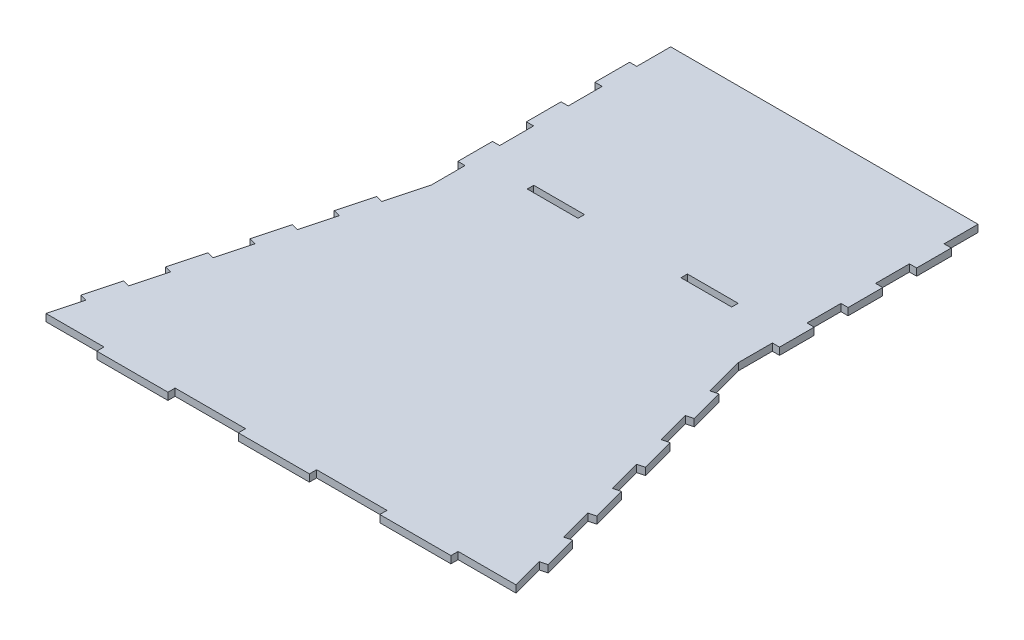
SolidWorks part; units mm, degrees
ref_plane "Front Plane" through (0, 0, 0) normal (0, 0, 1) x (1, 0, 0)
ref_plane "Top Plane" through (0, 0, 0) normal (0, 1, 0) x (1, 0, 0)
ref_plane "Right Plane" through (0, 0, 0) normal (1, 0, 0) x (0, 0, -1)
sketch "Sketch1" plane through (0, 0, 0) normal (0, 1, 0) x (1, 0, 0)
  line L0 (44.226, 0) -> (73.91, 0)
  line L1 (73.91, 0) -> (73.91, 3)
  line L3 (44.226, 3) -> (44.226, 0)
  line L4 (-14.842, 0) -> (14.842, 0)
  line L5 (14.842, 0) -> (14.842, 3)
  line L7 (-14.842, 3) -> (-14.842, 0)
  line L8 (-73.91, 0) -> (-44.226, 0)
  line L9 (-44.226, 0) -> (-44.226, 3)
  line L11 (-73.91, 3) -> (-73.91, 0)
  line L12 (-98.1297, 3) -> (-94.5922, 16.2024)
  line L13 (-94.5922, 16.2024) -> (-97.4899, 16.9788)
  line L14 (-97.4899, 16.9788) -> (-93.728, 31.0185)
  line L15 (-93.728, 31.0185) -> (-90.8303, 30.242)
  line L16 (-90.8303, 30.242) -> (-87.146, 43.9919)
  line L17 (-87.146, 43.9919) -> (-90.0438, 44.7684)
  line L18 (-90.0438, 44.7684) -> (-86.2819, 58.808)
  line L19 (-86.2819, 58.808) -> (-83.3841, 58.0316)
  line L20 (-83.3841, 58.0316) -> (-79.6998, 71.7814)
  line L21 (-79.6998, 71.7814) -> (-82.5976, 72.5579)
  line L22 (-82.5976, 72.5579) -> (-78.8357, 86.5976)
  line L23 (-78.8357, 86.5976) -> (-75.9379, 85.8211)
  line L24 (-75.9379, 85.8211) -> (-72.2536, 99.571)
  line L25 (-72.2536, 99.571) -> (-75.1514, 100.3474)
  line L26 (-75.1514, 100.3474) -> (-71.3895, 114.3871)
  line L27 (-71.3895, 114.3871) -> (-68.4917, 113.6106)
  line L28 (-68.4917, 113.6106) -> (-64.1503, 129.813)
  line L29 (-73.91, 3) -> (-98.1297, 3)
  line L30 (-44.226, 3) -> (-14.842, 3)
  line L31 (14.842, 3) -> (44.226, 3)
  line L32 (0, -16.1228) -> (0, 54.6201) construction
  line L33 (73.91, 3) -> (98.1297, 3)
  line L34 (-73.91, 3) -> (-44.526, 3) construction
  line L35 (-44.526, 3) -> (-44.226, 3) construction
  line L36 (-94.5922, 16.2024) -> (-90.9079, 29.9522) construction
  line L37 (-90.9079, 29.9522) -> (-90.8303, 30.242) construction
  line L38 (98.1297, 3) -> (94.5922, 16.2024)
  line L39 (90.9079, 29.9522) -> (90.8303, 30.242) construction
  line L40 (94.5922, 16.2024) -> (90.9079, 29.9522) construction
  line L41 (68.4917, 113.6106) -> (64.1503, 129.813)
  line L42 (71.3895, 114.3871) -> (68.4917, 113.6106)
  line L43 (75.1514, 100.3474) -> (71.3895, 114.3871)
  line L44 (72.2536, 99.571) -> (75.1514, 100.3474)
  line L45 (75.9379, 85.8211) -> (72.2536, 99.571)
  line L46 (78.8357, 86.5976) -> (75.9379, 85.8211)
  line L47 (82.5976, 72.5579) -> (78.8357, 86.5976)
  line L48 (79.6998, 71.7814) -> (82.5976, 72.5579)
  line L49 (83.3841, 58.0316) -> (79.6998, 71.7814)
  line L50 (86.2819, 58.808) -> (83.3841, 58.0316)
  line L51 (90.0438, 44.7684) -> (86.2819, 58.808)
  line L52 (87.146, 43.9919) -> (90.0438, 44.7684)
  line L53 (90.8303, 30.242) -> (87.146, 43.9919)
  line L54 (93.728, 31.0185) -> (90.8303, 30.242)
  line L55 (97.4899, 16.9788) -> (93.728, 31.0185)
  line L56 (94.5922, 16.2024) -> (97.4899, 16.9788)
  line L57 (-64.1503, 129.813) -> (-64.1503, 143.9701)
  line L58 (-64.1503, 143.9701) -> (-67.1503, 143.9701)
  line L59 (-67.1503, 143.9701) -> (-67.1503, 158.4273)
  line L60 (-67.1503, 158.4273) -> (-64.1503, 158.4273)
  line L61 (-64.1503, 158.4273) -> (-64.1503, 172.5844)
  line L62 (-64.1503, 172.5844) -> (-67.1503, 172.5844)
  line L63 (-67.1503, 172.5844) -> (-67.1503, 187.0416)
  line L64 (-67.1503, 187.0416) -> (-64.1503, 187.0416)
  line L65 (-64.1503, 187.0416) -> (-64.1503, 201.1987)
  line L66 (-64.1503, 201.1987) -> (-67.1503, 201.1987)
  line L67 (-67.1503, 201.1987) -> (-67.1503, 215.6559)
  line L68 (-67.1503, 215.6559) -> (-64.1503, 215.6559)
  line L69 (-64.1503, 215.6559) -> (-64.1503, 229.813)
  line L70 (-64.1503, 229.813) -> (64.1503, 229.813)
  line L71 (-64.1503, 143.9701) -> (-64.1503, 158.1273) construction
  line L72 (-64.1503, 158.1273) -> (-64.1503, 158.4273) construction
  line L73 (64.1503, 158.1273) -> (64.1503, 158.4273) construction
  line L74 (64.1503, 143.9701) -> (64.1503, 158.1273) construction
  line L75 (64.1503, 215.6559) -> (64.1503, 229.813)
  line L76 (67.1503, 215.6559) -> (64.1503, 215.6559)
  line L77 (67.1503, 201.1987) -> (67.1503, 215.6559)
  line L78 (64.1503, 201.1987) -> (67.1503, 201.1987)
  line L79 (64.1503, 187.0416) -> (64.1503, 201.1987)
  line L80 (67.1503, 187.0416) -> (64.1503, 187.0416)
  line L81 (67.1503, 172.5844) -> (67.1503, 187.0416)
  line L82 (64.1503, 172.5844) -> (67.1503, 172.5844)
  line L83 (64.1503, 158.4273) -> (64.1503, 172.5844)
  line L84 (67.1503, 158.4273) -> (64.1503, 158.4273)
  line L85 (67.1503, 143.9701) -> (67.1503, 158.4273)
  line L86 (64.1503, 143.9701) -> (67.1503, 143.9701)
  line L87 (64.1503, 129.813) -> (64.1503, 143.9701)
  line L88 (-42.6669, 148.463) -> (-21.4834, 148.463)
  line L89 (-42.6669, 148.463) -> (-42.6669, 151.163)
  line L90 (-21.4834, 148.463) -> (-21.4834, 151.163)
  line L91 (-42.6669, 151.163) -> (-21.4834, 151.163)
  line L92 (-42.6669, 149.813) -> (-64.1503, 149.813) construction
  line L93 (-21.4834, 149.813) -> (0, 149.813) construction
  line L94 (-21.4834, 150.488) -> (-42.9669, 150.488) construction
  line L95 (-42.9669, 150.488) -> (-42.6669, 150.488) construction
  line L96 (-21.4834, 149.813) -> (-42.6669, 151.163) construction
  line L97 (21.4834, 148.463) -> (21.4834, 151.163)
  line L98 (42.6669, 151.163) -> (21.4834, 151.163)
  line L99 (42.6669, 148.463) -> (42.6669, 151.163)
  line L100 (42.6669, 148.463) -> (21.4834, 148.463)
  point P32 (0, 0)
  point P85 (0, 229.813)
  point P95 (-32.0751, 150.488)
  dimension "D1" = 75
  dimension "D2" = 196.2595
  dimension "D3" = 24.2197
  dimension "D4" = 3
  dimension "D5" = 0.3
  dimension "D6" = 13.6681
  dimension "D7" = 16.7739
  dimension "D8" = 131.2865
  dimension "D9" = 0.3
  dimension "D10" = 100
  dimension "D11" = 80
  dimension "D12" = 2.7
  dimension "D13" = 0.3
extrude "Boss-Extrude1" add sketch "Sketch1" along normal blind 3
